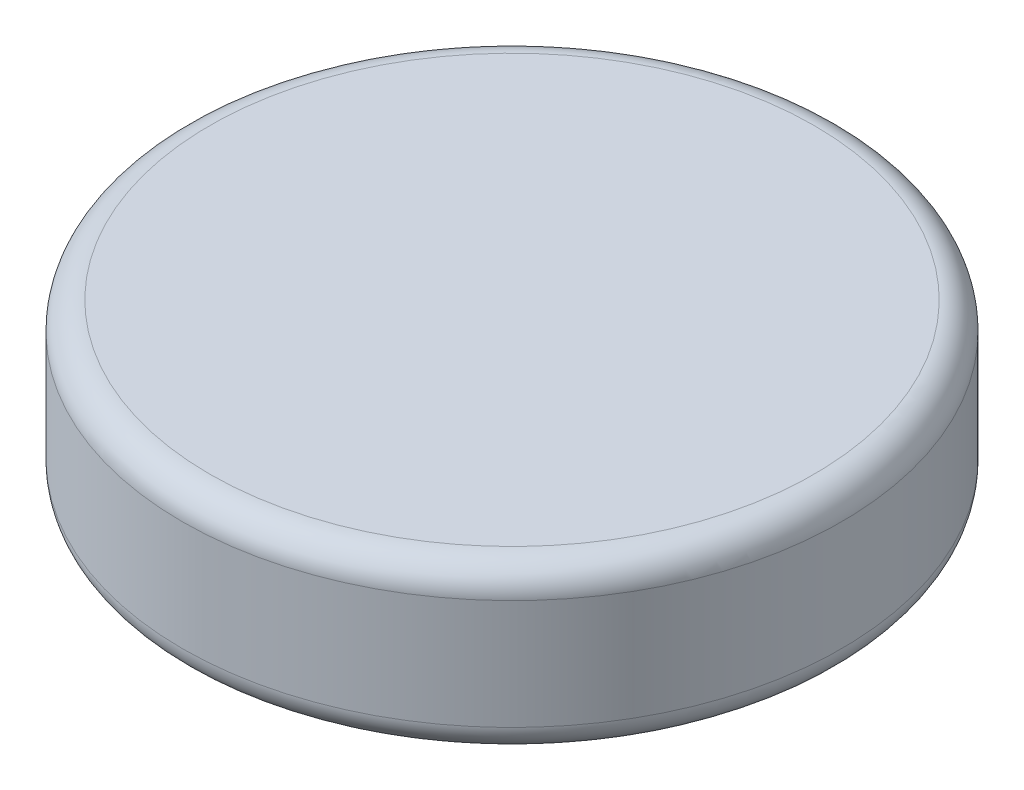
SolidWorks part; units mm, degrees
ref_plane "Front Plane" through (0, 0, 0) normal (0, 0, 1) x (1, 0, 0)
ref_plane "Top Plane" through (0, 0, 0) normal (0, 1, 0) x (1, 0, 0)
ref_plane "Right Plane" through (0, 0, 0) normal (1, 0, 0) x (0, 0, -1)
sketch "Sketch1" plane through (0, 0, 0) normal (0, 1, 0) x (1, 0, 0)
  circle A0 centre (0, 0) radius 5.9995
  dimension "D1" = 11.999
extrude "Boss-Extrude1" add sketch "Sketch1" along normal blind 3
fillet "Fillet1" radius 0.5 2 edges at (0, 0, 5.9995) (0, 3, 5.9995)
